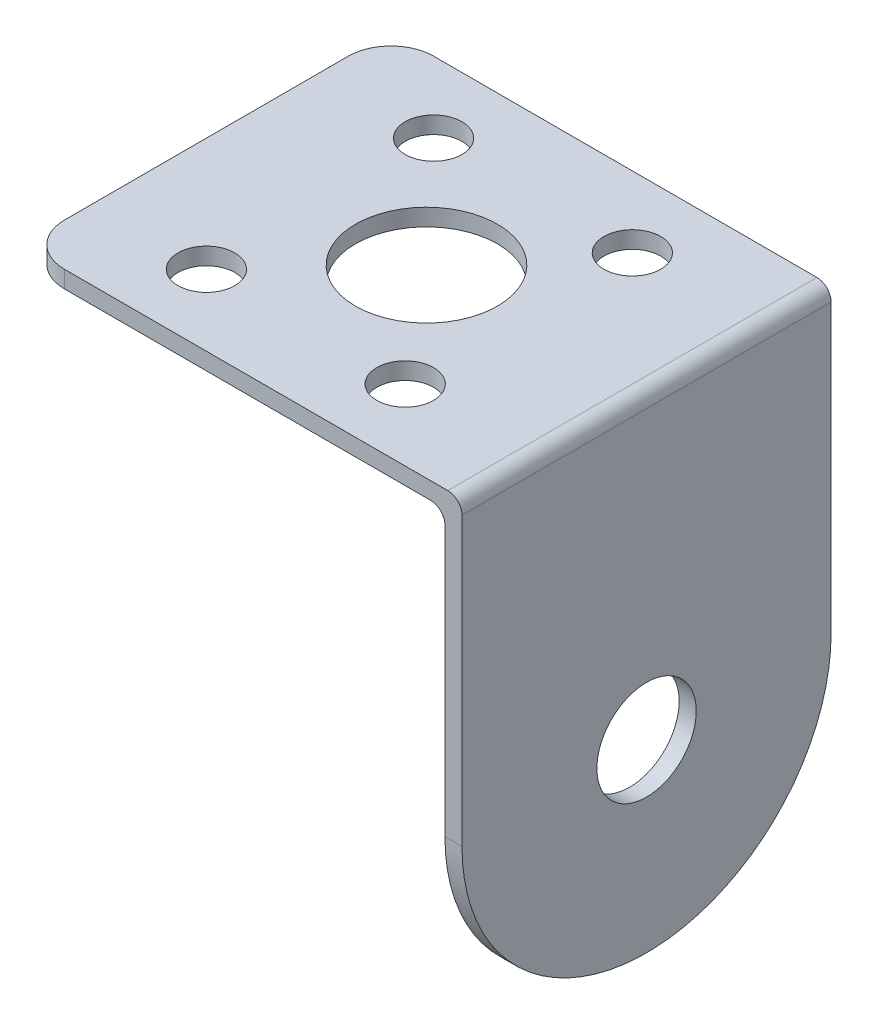
SolidWorks part; units mm, degrees
ref_plane "Front Plane" through (0, 0, 0) normal (0, 0, 1) x (1, 0, 0)
ref_plane "Top Plane" through (0, 0, 0) normal (0, 1, 0) x (1, 0, 0)
ref_plane "Right Plane" through (0, 0, 0) normal (1, 0, 0) x (0, 0, -1)
sketch "Sketch1" plane through (0, 0, 0) normal (0, 1, 0) x (1, 0, 0)
  line L1 (15.5, 13) -> (-15.5, 13)
  line L2 (15.5, 13) -> (15.5, -13)
  line L3 (15.5, -13) -> (-15.5, -13)
  line L4 (-15.5, 13) -> (-15.5, -13)
  line L5 (15.5, 13) -> (-15.5, -13) construction
  line L6 (15.5, -13) -> (-15.5, 13) construction
  point P0 (0, 0)
  dimension "D1" = 26
  dimension "D2" = 31
extrude "Boss-Extrude1" add sketch "Sketch1" along normal blind 1.2
sketch "Sketch2" plane through (0, 1.2, 0) normal (0, 1, 0) x (1, 0, 0)
  line L0 (-15.5, 8) -> (-7.5, 8) construction
  line L1 (-15.5, 13) -> (-15.5, -13) construction
  line L2 (-7.5, 8) -> (6.5, 8) construction
  line L5 (-15.5, 0) -> (15.5, 0) construction
  line L6 (15.5, -13) -> (15.5, 13) construction
  line L7 (-7.5, 0) -> (-7.5, 8) construction
  circle A0 centre (0, 0) radius 5
  circle A2 centre (-7.5, 8) radius 2
  circle A3 centre (6.5, 8) radius 2
  circle A4 centre (6.5, -8) radius 2
  circle A5 centre (-7.5, -8) radius 2
  dimension "D2" = 10
  dimension "D4" = 4
  dimension "D1" = 8
  dimension "D3" = 8
  dimension "D5" = 14
sketch "Sketch3" plane through (0, 0, 0) normal (0, -1, 0) x (1, 0, 0)
  line L0 (15.5, -13) -> (-15.5, -13) construction
  line L1 (15.5, 13) -> (14.3, 13)
  line L2 (15.5, 13) -> (15.5, -13)
  line L3 (15.5, -13) -> (14.3, -13)
  line L4 (14.3, 13) -> (14.3, -13)
  line L5 (15.5, 13) -> (14.3, -13) construction
  line L6 (15.5, -13) -> (14.3, 13) construction
  point P4 (14.9, 0)
  dimension "D1" = 1.2
extrude "Boss-Extrude2" add sketch "Sketch3" along normal blind 33
sketch "Sketch4" plane through (15.5, 0, 0) normal (1, 0, 0) x (0, 0, -1)
  line L1 (13, -20) -> (13, -33)
  line L2 (13, -33) -> (0, -33)
  line L3 (0, -33) -> (-13, -33)
  line L4 (-13, -33) -> (-13, -20)
  arc A0 (-13, -20) -> (13, -20) centre (0, -20) ccw
  arc A1 (13, -20) -> (-13, -20) centre (0, -20) ccw construction
  circle A2 centre (0, -20) radius 3.5
  line M3 (-13, 1.2) -> (-13, -33)
  line M4 (-13, -33) -> (13, -33)
  line M5 (13, -33) -> (13, 1.2)
  dimension "D1" = 7
extrude "Cut-Extrude1" cut sketch "Sketch4" against normal up to surface (1.2 mm away) contours A0 M4 M5 | A0 M3 M4 | A2 up to face at (14.3, -16.5, 0)
extrude "Cut-Extrude2" cut sketch "Sketch2" against normal up to surface (1.2 mm away) up to face at (-0.6, 0, 0)
fillet "Fillet1" radius 1 2 edges at (14.3, 0, 0) (15.5, 1.2, 0)
fillet "Fillet2" radius 3 2 edges at (-15.5, 0.6, -13) (-15.5, 0.6, 13)
